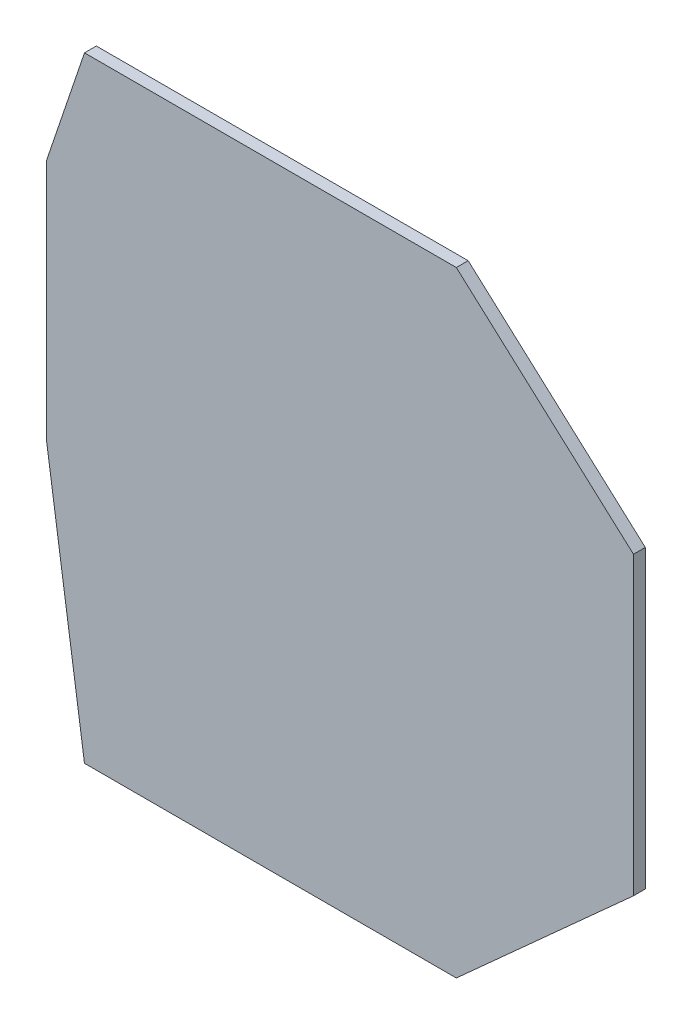
SolidWorks part; units mm, degrees
ref_plane "Спереди" through (0, 0, 0) normal (0, 0, 1) x (1, 0, 0)
ref_plane "Сверху" through (0, 0, 0) normal (0, 1, 0) x (1, 0, 0)
ref_plane "Справа" through (0, 0, 0) normal (1, 0, 0) x (0, 0, -1)
other "Configuration Table"
sketch "Эскиз2" plane through (0, 0, 0) normal (0, 0, 1) x (1, 0, 0)
  line L2 (-49.7727, 143.2) -> (50.7868, 143.2)
  line L20 (-60, 47.016) -> (-49.7727, -23.2)
  line L21 (-60, 112.984) -> (-60, 47.016)
  line L22 (-49.7727, 143.2) -> (-60, 112.984)
  line L23 (98.6981, 100) -> (98.6981, 20)
  line L27 (-60, -23.2) -> (50.7868, -23.2)
  line L29 (140, 57.2406) -> (140, 62.7594)
  line L30 (50.7868, -23.2) -> (140, 57.2406)
  line L35 (140, 62.7594) -> (50.7868, 143.2)
  line L36 (50.7868, 143.2) -> (-60, 143.2)
  line L37 (-49.7727, -23.2) -> (50.7868, -23.2)
  line L39 (50.7868, -23.2) -> (98.6981, 20)
  line L40 (98.6981, 100) -> (50.7868, 143.2)
  dimension "D1" = 80
  dimension "D2" = 50
extrude "Бобышка-Вытянуть1" add sketch "Эскиз2" along normal blind 3.2
